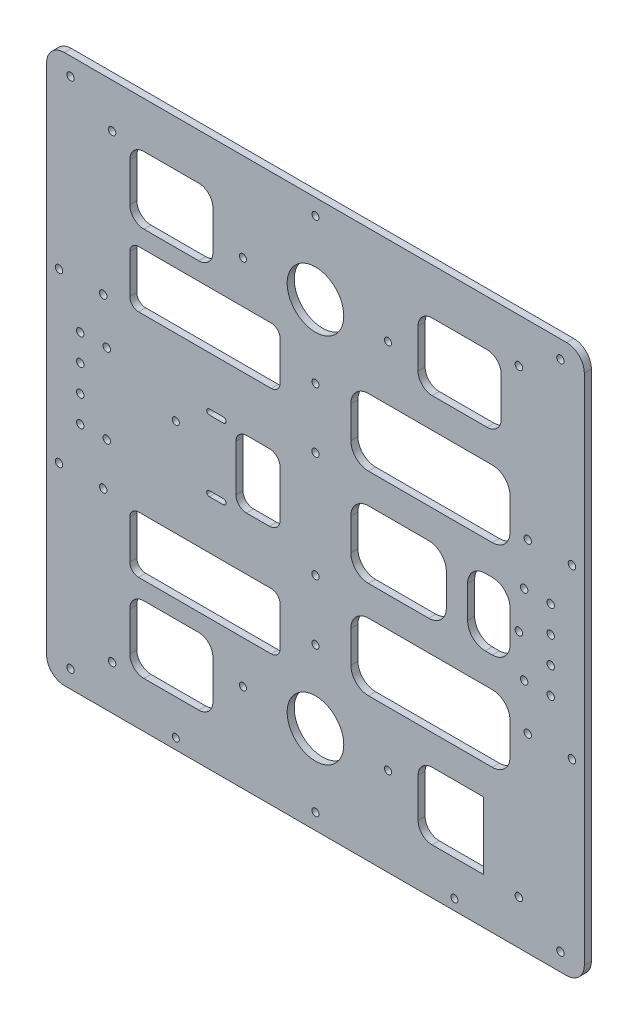
SolidWorks part; units mm, degrees
ref_plane "前视基准面" through (0, 0, 0) normal (0, 0, 1) x (1, 0, 0)
ref_plane "上视基准面" through (0, 0, 0) normal (0, 1, 0) x (1, 0, 0)
ref_plane "右视基准面" through (0, 0, 0) normal (1, 0, 0) x (0, 0, -1)
ref_plane "基准面1" through (0, 0, 0) normal (0, 0, -1) x (-1, 0, 0)
sketch "草图1" plane through (0, 0, 0) normal (0, 0, -1) x (-1, 0, 0)
  line L1 (142, 155) -> (-142, 155)
  line L3 (-142, -155) -> (142, -155)
  line L4 (152, 145) -> (152, -145)
  line L5 (-152, 145) -> (-152, -145)
  line L8 (60, -21.5) -> (52, -21.5)
  line L9 (52, -18.5) -> (60, -18.5)
  line L10 (60, 18.5) -> (52, 18.5)
  line L11 (52, 21.5) -> (60, 21.5)
  line L12 (-100, -36) -> (-30, -36)
  line L13 (-20, -46) -> (-20, -64)
  line L14 (-30, -74) -> (-100, -74)
  line L15 (-110, -64) -> (-110, -46)
  line L16 (-100, 19) -> (-30, 19)
  line L17 (-20, 9) -> (-20, -9)
  line L18 (-30, -19) -> (-100, -19)
  line L19 (-110, -9) -> (-110, 9)
  line L20 (-100, 74) -> (-30, 74)
  line L21 (-20, 64) -> (-20, 46)
  line L22 (-30, 36) -> (-100, 36)
  line L23 (-110, 46) -> (-110, 64)
  line L24 (25, 81) -> (100, 81)
  line L25 (105, 76) -> (105, 54)
  line L26 (100, 49) -> (25, 49)
  line L27 (20, 54) -> (20, 76)
  line L28 (25, -49) -> (100, -49)
  line L29 (105, -54) -> (105, -76)
  line L30 (100, -81) -> (25, -81)
  line L31 (20, -76) -> (20, -54)
  line L32 (-97, 129) -> (-58, 129)
  line L33 (-50, 121) -> (-50, 99)
  line L34 (-58, 91) -> (-97, 91)
  line L35 (-105, 99) -> (-105, 121)
  line L36 (97, 91) -> (58, 91)
  line L37 (50, 99) -> (50, 121)
  line L38 (58, 129) -> (97, 129)
  line L39 (105, 121) -> (105, 99)
  line L40 (39, -19) -> (26, -19)
  line L41 (20, -13) -> (20, 13)
  line L42 (26, 19) -> (39, 19)
  line L43 (45, 13) -> (45, -13)
  line L44 (97, -129) -> (58, -129)
  line L45 (50, -121) -> (50, -99)
  line L46 (58, -91) -> (97, -91)
  line L47 (105, -99) -> (105, -121)
  line L48 (-97, -91) -> (-58, -91)
  line L49 (-50, -99) -> (-50, -121)
  line L50 (-58, -129) -> (-97, -129)
  line L51 (-105, -121) -> (-105, -99)
  circle A0 centre (0, 63.9878) radius 2.1
  circle A1 centre (0, 146.0122) radius 2.1
  circle A2 centre (0, -146.0122) radius 2.1
  circle A3 centre (41, 105) radius 2
  circle A4 centre (0, -105) radius 16
  arc A5 (142, -155) -> (152, -145) centre (142, -145) ccw
  arc A6 (-142, -155) -> (-152, -145) centre (-142, -145) cw
  circle A9 centre (0, 105) radius 16
  circle A10 centre (0, -63.9878) radius 2.1
  circle A11 centre (-41, -105) radius 2
  circle A12 centre (41, -105) radius 2
  circle A13 centre (-41, 105) radius 2
  circle A14 centre (120, 47.5) radius 2.1
  circle A15 centre (-145, 47.5) radius 2.1
  circle A16 centre (-145, -47.5) radius 2.1
  circle A17 centre (-120, -47.5) radius 2.1
  circle A18 centre (120, -47.5) radius 2.1
  circle A19 centre (145, -47.5) radius 2.1
  circle A20 centre (-115, 0) radius 2.1
  circle A21 centre (145, 47.5) radius 2.1
  circle A22 centre (0, -30) radius 2.1
  circle A23 centre (0, 30) radius 2.1
  circle A24 centre (115, 130) radius 2.1
  circle A25 centre (115, -130) radius 2.1
  circle A26 centre (-115, -130) radius 2.1
  circle A27 centre (-115, 130) radius 2.1
  circle A28 centre (-120, 47.5) radius 2.1
  arc A29 (-152, 145) -> (-142, 155) centre (-142, 145) cw
  arc A30 (142, 155) -> (152, 145) centre (142, 145) cw
  arc A34 (60, -18.5) -> (60, -21.5) centre (60, -20) cw
  arc A35 (52, -21.5) -> (52, -18.5) centre (52, -20) cw
  arc A37 (60, 21.5) -> (60, 18.5) centre (60, 20) cw
  arc A38 (52, 18.5) -> (52, 21.5) centre (52, 20) cw
  arc A39 (-110, -46) -> (-100, -36) centre (-100, -46) cw
  arc A40 (-30, -36) -> (-20, -46) centre (-30, -46) cw
  arc A41 (-20, -64) -> (-30, -74) centre (-30, -64) cw
  arc A42 (-100, -74) -> (-110, -64) centre (-100, -64) cw
  arc A43 (-110, 9) -> (-100, 19) centre (-100, 9) cw
  arc A44 (-30, 19) -> (-20, 9) centre (-30, 9) cw
  arc A45 (-20, -9) -> (-30, -19) centre (-30, -9) cw
  arc A46 (-100, -19) -> (-110, -9) centre (-100, -9) cw
  arc A47 (-110, 64) -> (-100, 74) centre (-100, 64) cw
  arc A48 (-30, 74) -> (-20, 64) centre (-30, 64) cw
  arc A49 (-20, 46) -> (-30, 36) centre (-30, 46) cw
  arc A50 (-100, 36) -> (-110, 46) centre (-100, 46) cw
  arc A51 (20, 76) -> (25, 81) centre (25, 76) cw
  arc A52 (100, 81) -> (105, 76) centre (100, 76) cw
  arc A53 (105, 54) -> (100, 49) centre (100, 54) cw
  arc A54 (25, 49) -> (20, 54) centre (25, 54) cw
  arc A55 (20, -54) -> (25, -49) centre (25, -54) cw
  arc A56 (100, -49) -> (105, -54) centre (100, -54) cw
  arc A57 (105, -76) -> (100, -81) centre (100, -76) cw
  arc A58 (25, -81) -> (20, -76) centre (25, -76) cw
  arc A59 (-105, 121) -> (-97, 129) centre (-97, 121) cw
  arc A60 (-58, 129) -> (-50, 121) centre (-58, 121) cw
  arc A61 (-50, 99) -> (-58, 91) centre (-58, 99) cw
  arc A62 (-97, 91) -> (-105, 99) centre (-97, 99) cw
  arc A63 (105, 99) -> (97, 91) centre (97, 99) cw
  arc A64 (58, 91) -> (50, 99) centre (58, 99) cw
  arc A65 (50, 121) -> (58, 129) centre (58, 121) cw
  arc A66 (97, 129) -> (105, 121) centre (97, 121) cw
  arc A67 (45, -13) -> (39, -19) centre (39, -13) cw
  arc A68 (26, -19) -> (20, -13) centre (26, -13) cw
  arc A69 (20, 13) -> (26, 19) centre (26, 13) cw
  arc A70 (39, 19) -> (45, 13) centre (39, 13) cw
  arc A71 (105, -121) -> (97, -129) centre (97, -121) cw
  arc A72 (58, -129) -> (50, -121) centre (58, -121) cw
  arc A73 (50, -99) -> (58, -91) centre (58, -99) cw
  arc A74 (97, -91) -> (105, -99) centre (97, -99) cw
  arc A75 (-105, -99) -> (-97, -91) centre (-97, -99) cw
  arc A76 (-58, -91) -> (-50, -99) centre (-58, -99) cw
  arc A77 (-50, -121) -> (-58, -129) centre (-58, -121) cw
  arc A78 (-97, -129) -> (-105, -121) centre (-97, -121) cw
  dimension "D1" = 10
  dimension "D2" = 7
  dimension "D3" = 7
  dimension "D4" = 32
  dimension "D5" = 82
  dimension "D7" = 41
  dimension "D8" = 41
  dimension "D9" = 4
  dimension "D10" = 4
  dimension "D6" = 41
  dimension "D11" = 4
  dimension "D12" = 4
extrude "凸台-拉伸1" add sketch "草图1" against normal blind 4
sketch "草图2" plane through (0, 0, 0) normal (0, 0, -1) x (-1, 0, 0)
  line L0 (-152, 145) -> (-152, -145) construction
  line L1 (142, 155) -> (-142, 155) construction
  line L2 (152, -145) -> (152, 145) construction
  line L3 (-142, -155) -> (142, -155) construction
  circle A0 centre (-138.5, 145) radius 2.1
  circle A1 centre (138.5, 145) radius 2.1
  circle A2 centre (138.5, -145) radius 2.1
  circle A3 centre (-138.5, -145) radius 2.1
  dimension "D1" = 4.2
  dimension "D2" = 4.2
  dimension "D3" = 4.2
  dimension "D4" = 4.2
  dimension "D5" = 13.5
  dimension "D6" = 10
  dimension "D7" = 10
  dimension "D8" = 13.5
  dimension "D10" = 13.5
  dimension "D11" = 10
  dimension "D12" = 13.5
  dimension "D9" = 10
extrude "切除-拉伸1" cut sketch "草图2" against normal up to next
sketch "草图3" plane through (0, 0, 0) normal (0, 0, -1) x (-1, 0, 0)
  line L0 (152, -145) -> (152, 145) construction
  line L1 (142, 155) -> (-142, 155) construction
  line L2 (-142, -155) -> (142, -155) construction
  circle A0 centre (133, 7.5) radius 2.1
  circle A1 centre (133, -7.5) radius 2.1
  circle A2 centre (133, -22.5) radius 2.1
  circle A3 centre (133, 22.5) radius 2.1
  dimension "D1" = 19
  dimension "D2" = 4.2
  dimension "D3" = 4.2
  dimension "D5" = 147.5
  dimension "D6" = 4.2
  dimension "D7" = 4.2
  dimension "D9" = 15
  dimension "D4" = 147.5
  dimension "D8" = 15
extrude "切除-拉伸2" cut sketch "草图3" against normal up to next
ref_plane "基准面2" through (0, 0, 0) normal (-1, 0, 0) x (0, 0, 1)
mirror "镜向1" about plane through (0, 0, 0) normal (-1, 0, 0) of "切除-拉伸2"
sketch "草图4" plane through (0, 0, 0) normal (0, 0, -1) x (-1, 0, 0)
  circle A0 centre (-118, 22.5) radius 2.1
  circle A2 centre (-133, 22.5) radius 2.1 construction
  circle A4 centre (-118, -22.5) radius 2.1
  dimension "D1" = 4.2
  dimension "D2" = 4.2
  dimension "D3" = 15
extrude "切除-拉伸3" cut sketch "草图4" against normal up to next
mirror "镜向2" about plane through (0, 0, 0) normal (-1, 0, 0) of "切除-拉伸3"
sketch "草图5" plane through (0, 0, 0) normal (0, 0, -1) x (-1, 0, 0)
  line L1 (-58, 129) -> (-48.9256, 129)
  line L2 (-58, 129) -> (-58, 89.5706)
  line L3 (-58, 89.5706) -> (-48.9256, 89.5706)
  line L4 (-48.9256, 129) -> (-48.9256, 89.5706)
  line L5 (58, 129) -> (48.8834, 129)
  line L6 (58, 129) -> (58, 90.9396)
  line L7 (58, 90.9396) -> (48.8834, 90.9396)
  line L8 (48.8834, 129) -> (48.8834, 90.9396)
extrude "凸台-拉伸2" add sketch "草图5" against normal blind 4
fillet "圆角1" radius 8 4 edges at (58, 91, 2) (58, 129, 2) (-58, 91, 2) (-58, 129, 2)
sketch "草图6" plane through (0, 0, 0) normal (0, 0, -1) x (-1, 0, 0)
  line L1 (-58, -91) -> (-49.2334, -91)
  line L2 (-58, -91) -> (-58, -130.4131)
  line L3 (-58, -130.4131) -> (-49.2334, -130.4131)
  line L4 (-49.2334, -91) -> (-49.2334, -130.4131)
  line L5 (58, -91) -> (50, -91)
  line L6 (58, -91) -> (58, -130.4131)
  line L7 (58, -130.4131) -> (50, -130.4131)
  line L8 (50, -91) -> (50, -130.4131)
extrude "凸台-拉伸3" add sketch "草图6" against normal blind 4
fillet "圆角2" radius 8 4 edges at (-58, -129, 2) (-58, -91, 2) (58, -129, 2) (58, -91, 2)
sketch "草图7" plane through (0, 0, 0) normal (0, 0, -1) x (-1, 0, 0)
  line L0 (0, -2.2) -> (0, 2.2) construction
  circle A0 centre (0, 146) radius 2
  circle A1 centre (0, 64) radius 2
  circle A2 centre (0, -64) radius 2
  circle A3 centre (0, -146) radius 2
  circle A4 centre (0, -105) radius 16 construction
  circle A5 centre (0, 105) radius 16 construction
  dimension "D1" = 4
  dimension "D2" = 4
  dimension "D3" = 4
  dimension "D4" = 4
  dimension "D6" = 41
  dimension "D7" = 41
  dimension "D8" = 41
  dimension "D5" = 41
sketch "草图8" plane through (0, 0, 0) normal (0, 0, -1) x (-1, 0, 0)
  line L1 (-6.4003, 151.5607) -> (10.0114, 151.5607)
  line L2 (-6.4003, 151.5607) -> (-6.4003, 135.8785)
  line L3 (-6.4003, 135.8785) -> (10.0114, 135.8785)
  line L4 (10.0114, 151.5607) -> (10.0114, 135.8785)
  line L5 (-6.4003, 67.3143) -> (4.5408, 67.3143)
  line L6 (-6.4003, 67.3143) -> (-6.4003, 57.1027)
  line L7 (-6.4003, 57.1027) -> (4.5408, 57.1027)
  line L8 (4.5408, 67.3143) -> (4.5408, 57.1027)
  line L18 (-6.4003, -56.3887) -> (6.6762, -56.3887)
  line L19 (-6.4003, -56.3887) -> (-6.4003, -73.5546)
  line L20 (-6.4003, -73.5546) -> (6.6762, -73.5546)
  line L21 (6.6762, -56.3887) -> (6.6762, -73.5546)
  line L22 (-8.8257, -138.7481) -> (6.6762, -138.7481)
  line L23 (-8.8257, -138.7481) -> (-8.8257, -151.8346)
  line L24 (-8.8257, -151.8346) -> (6.6762, -151.8346)
  line L25 (6.6762, -138.7481) -> (6.6762, -151.8346)
extrude "凸台-拉伸4" add sketch "草图8" against normal blind 4
extrude "切除-拉伸4" cut sketch "草图7" against normal up to next
sketch "草图9" plane through (0, 0, 0) normal (0, 0, -1) x (-1, 0, 0)
  line L3 (-142, -155) -> (142, -155) construction
  circle A4 centre (78.9572, -149) radius 2
  circle A5 centre (78.9572, 6) radius 2
  circle A6 centre (-78.5428, -149) radius 2
  dimension "D1" = 6
  dimension "D4" = 4
  dimension "D5" = 155
  dimension "D2" = 4
  dimension "D3" = 4
  dimension "D6" = 157.5
  dimension "D7" = 6
extrude "切除-拉伸5" cut sketch "草图9" against normal blind 10
sketch "草图10" plane through (0, 0, 0) normal (0, 0, -1) x (-1, 0, 0)
  line L0 (-86, 19) -> (-86, -19)
  line L1 (-30, 19) -> (-100, 19) construction
  line L2 (-100, -19) -> (-30, -19) construction
  line L3 (-86, -19) -> (-74, -19)
  line L4 (-74, -19) -> (-74, 19)
  line L5 (-74, 19) -> (-86, 19)
  line L6 (-110, 9) -> (-110, -9) construction
  dimension "D1" = 24
  dimension "D2" = 12
extrude "凸台-拉伸5" add sketch "草图10" against normal blind 4
fillet "圆角3" radius 10 4 edges at (74, -19, 2) (74, 19, 2) (86, -19, 2) (86, 19, 2)
sketch "草图12" plane through (0, 0, 0) normal (0, 0, -1) x (-1, 0, 0)
  line L0 (-95, -91) -> (-95, -129)
  line L1 (-66, -91) -> (-97, -91) construction
  line L2 (-97, -129) -> (-66, -129) construction
  line L3 (-95, -129) -> (-105.9015, -129)
  line L4 (-105.9015, -129) -> (-105.9015, -91)
  line L5 (-105.9015, -91) -> (-95, -91)
  line L6 (-105, -99) -> (-105, -121) construction
  dimension "D1" = 10
extrude "凸台-拉伸6" add sketch "草图12" against normal blind 4
